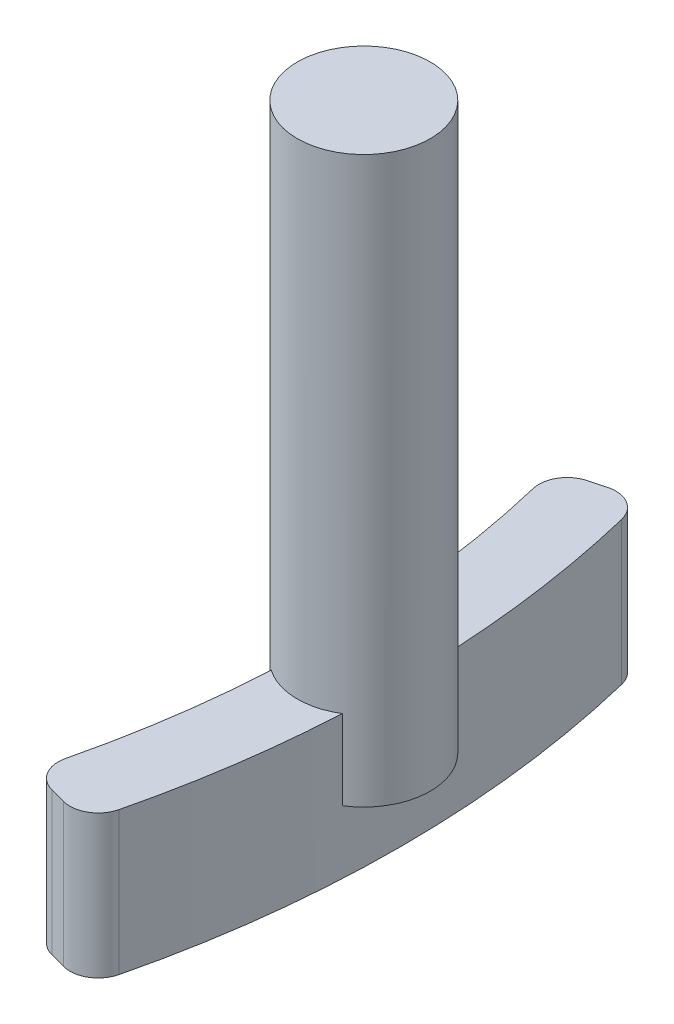
SolidWorks part; units mm, degrees
material "ABS"
ref_plane "Front Plane" through (0, 0, 0) normal (0, 0, 1) x (1, 0, 0)
ref_plane "Top Plane" through (0, 0, 0) normal (0, 1, 0) x (1, 0, 0)
ref_plane "Right Plane" through (0, 0, 0) normal (1, 0, 0) x (0, 0, -1)
sketch "Эскиз1" plane through (0, 0, 0) normal (0, 1, 0) x (1, 0, 0)
  line L12 (-0.9012, -8.0529) -> (-0.4181, -8.1824)
  line L13 (-0.9012, 8.0529) -> (-0.4181, 8.1824)
  arc A36 (0.6279, -7.5615) -> (-0.4181, -8.1824) centre (-0.1981, -7.3613) cw
  arc A37 (0.6279, -7.5615) -> (0.6279, 7.5615) centre (-30.5687, 0) ccw
  arc A38 (-0.4181, 8.1824) -> (0.6279, 7.5615) centre (-0.1981, 7.3613) cw
  arc A39 (-0.9012, 8.0529) -> (-1.5074, 7.032) centre (-0.6813, 7.2319) ccw
  arc A40 (-1.5074, -7.032) -> (-1.5074, 7.032) centre (-30.5687, 0) ccw
  arc A41 (-0.9012, -8.0529) -> (-1.5074, -7.032) centre (-0.6813, -7.2319) cw
  point P0 (0, 0)
extrude "Бобышка-Вытянуть1" add sketch "Эскиз1" along normal blind 4.3
ref_plane "Плоскость1" through (0, 1.9, 0) normal (0, 1, 0) x (1, 0, 0)
sketch "Эскиз2" plane through (0, 1.9, 0) normal (0, 1, 0) x (1, 0, 0)
  circle A2 centre (0.4313, 0) radius 2
  dimension "D1" = 4
extrude "Бобышка-Вытянуть2" add sketch "Эскиз2" along normal blind 17
